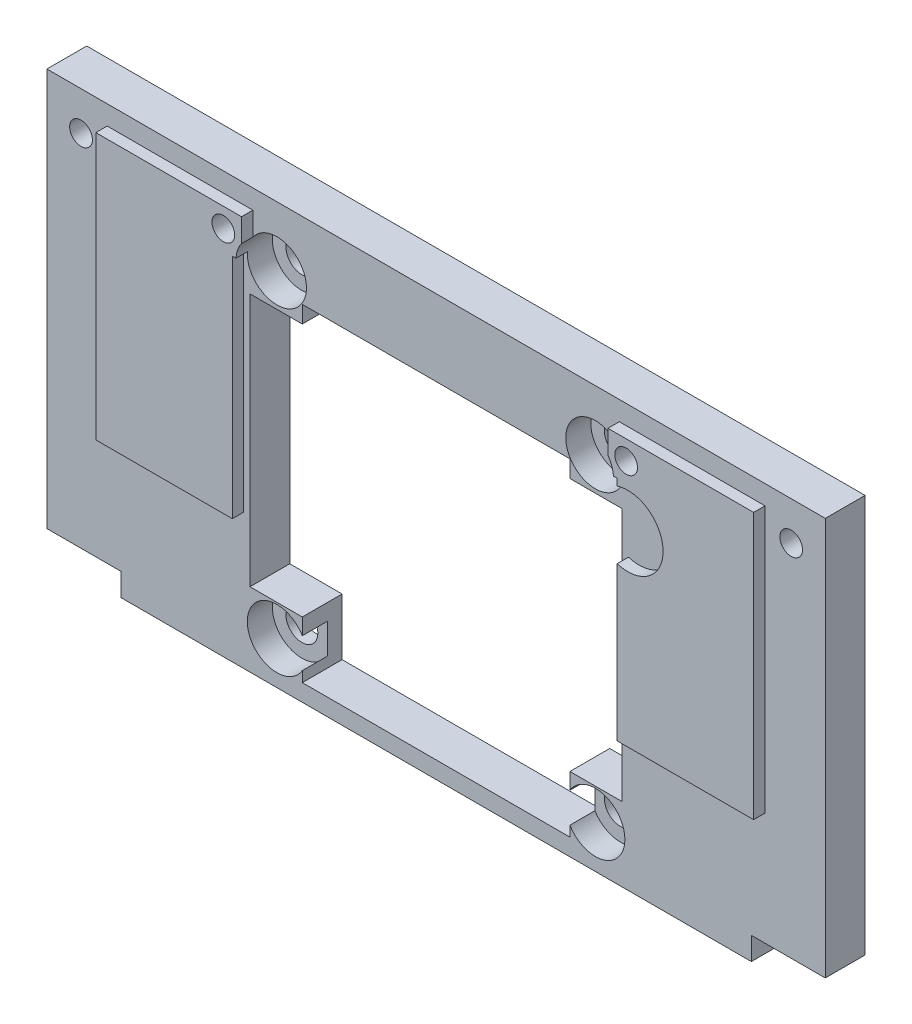
SolidWorks part; units mm, degrees
ref_plane "Front Plane" through (0, 0, 0) normal (0, 0, 1) x (1, 0, 0)
ref_plane "Top Plane" through (0, 0, 0) normal (0, 1, 0) x (1, 0, 0)
ref_plane "Right Plane" through (0, 0, 0) normal (1, 0, 0) x (0, 0, -1)
sketch "Sketch3" plane through (0, 0, 0) normal (0, 0, 1) x (1, 0, 0)
  line L0 (-37.4368, -0.9626) -> (-37.4368, 36.0374)
  line L1 (-3.2168, 30.7779) -> (-3.2168, 32.6429) construction
  line L2 (-34.7809, 21.6224) -> (-21.3928, 21.6224) construction
  line L3 (-30.5893, -0.9626) -> (18.3407, -0.9626) construction
  line L4 (-9.7818, 10.2129) -> (-9.7818, 23.3429) construction
  line L5 (-9.7818, 23.3429) -> (3.3482, 23.3429) construction
  line L6 (3.3482, 23.3429) -> (3.3482, 10.2129) construction
  line L7 (3.3482, 10.2129) -> (-9.7818, 10.2129) construction
  line L9 (-37.4368, -0.9626) -> (-14.8318, -0.9626)
  line L10 (-14.9818, 0.5374) -> (-14.9818, 5.5374)
  line L11 (-14.9818, 29.3429) -> (8.5482, 29.3429)
  line L12 (8.5482, 29.3429) -> (8.5482, 27.8429)
  line L13 (7.2982, -0.9626) -> (31.0032, -0.9626)
  line L14 (31.0032, -0.9626) -> (31.0032, 36.0374)
  line L15 (31.0032, 36.0374) -> (-37.4368, 36.0374)
  line L16 (-34.4368, 32.6429) -> (-20.9268, 32.6429) construction
  line L17 (-20.9268, 32.6429) -> (14.4932, 32.6429) construction
  line L18 (14.4932, 32.6429) -> (28.0032, 32.6429) construction
  line L19 (-17.2168, 30.7779) -> (10.7832, 30.7779) construction
  line L20 (-3.2168, 30.7779) -> (-3.2168, 23.3429) construction
  line L21 (-3.2168, 23.3429) -> (-3.2168, 10.2129) construction
  line L22 (-3.2168, 32.6429) -> (-3.2168, 42.2345) construction
  line L23 (-14.8318, -0.9626) -> (7.2982, -0.9626)
  line L24 (8.5482, 0.5374) -> (-14.9818, 0.5374)
  line L25 (-14.9818, 27.8429) -> (-19.5818, 27.8429)
  line L26 (-19.5818, 27.8429) -> (-19.5818, 5.5374)
  line L27 (-19.5818, 5.5374) -> (-14.9818, 5.5374)
  line L28 (-14.9818, 27.8429) -> (-14.9818, 29.3429)
  line L29 (8.5482, 5.5374) -> (13.1482, 5.5374)
  line L30 (13.1482, 5.5374) -> (13.1482, 27.8429)
  line L31 (13.1482, 27.8429) -> (8.5482, 27.8429)
  line L32 (8.5482, 5.5374) -> (8.5482, 0.5374)
  line L35 (-17.2168, 30.7779) -> (-17.2168, 2.7779) construction
  line L36 (-17.2168, 2.7779) -> (10.7832, 2.7779) construction
  line L37 (10.7832, 2.7779) -> (10.7832, 30.7779) construction
  circle A0 centre (-17.2168, 30.7779) radius 1.4
  circle A1 centre (-34.4368, 32.6429) radius 1
  circle A2 centre (-20.9268, 32.6429) radius 1
  circle A3 centre (14.4932, 32.6429) radius 1
  circle A4 centre (28.0032, 32.6429) radius 1
  circle A5 centre (-34.4368, 32.6429) radius 1
  circle A6 centre (-20.9268, 32.6429) radius 1
  circle A7 centre (-17.2168, 30.7779) radius 1.4
  circle A8 centre (-17.2168, 2.7779) radius 1.4
  circle A9 centre (10.7832, 30.7779) radius 1.4
  circle A10 centre (10.7832, 2.7779) radius 1.4
  point P47 (10.8482, 27.8429)
  dimension "D16" = 2
  dimension "D17" = 2.8
  dimension "D1" = 13.51
  dimension "D2" = 35.42
  dimension "D3" = 13.51
  dimension "D4" = 3.3945
  dimension "D5" = 28
  dimension "D6" = 1.865
  dimension "D7" = 13.13
  dimension "D8" = 13.13
  dimension "D9" = 7.435
  dimension "D10" = 3
  dimension "D11" = 3
  dimension "D12" = 5.2
  dimension "D13" = 5.2
  dimension "D14" = 6
  dimension "D15" = 37
  dimension "D18" = 1.5
  dimension "D19" = 5
  dimension "D20" = 9.8
  dimension "D22" = 1.5
  dimension "D23" = 9.8
  dimension "D24" = 28
extrude "Boss-Extrude1" add sketch "Sketch3" along normal blind 3.5 contours L14 L15 L0 L9 L10 L11 L12 L13 A9 A4 A3 A2 A1 A0
sketch "Sketch13" plane through (0, 0, 0) normal (0, 0, -1) x (-1, 0, 0)
  line L0 (-31.0032, 36.0374) -> (37.4368, 36.0374) construction
  line L1 (-31.0032, 36.0374) -> (-16.1332, 36.0374)
  line L2 (-31.0032, 36.0374) -> (-31.0032, -0.9626)
  line L3 (-31.0032, -0.9626) -> (-16.1332, -0.9626)
  line L4 (-16.1332, 36.0374) -> (-16.1332, -0.9626)
  line L5 (37.4368, -0.9626) -> (-31.0032, -0.9626) construction
  line L7 (22.5668, 36.0374) -> (37.4368, 36.0374)
  line L8 (22.5668, 36.0374) -> (22.5668, -0.9626)
  line L9 (22.5668, -0.9626) -> (37.4368, -0.9626)
  line L10 (37.4368, 36.0374) -> (37.4368, -0.9626)
  line L11 (3.2168, 36.0374) -> (3.2168, 44.4839) construction
  line L12 (3.2168, 36.0374) -> (-16.1332, 36.0374) construction
  line L13 (3.2168, 36.0374) -> (22.5668, 36.0374) construction
  line L14 (-31.0032, -0.9626) -> (-31.0032, 36.0374) construction
  dimension "D1" = 38.7
extrude "Boss-Extrude3" [suppressed] add sketch "Sketch13" along normal blind 1
sketch "Sketch9" plane through (0, 0, 3.5) normal (0, 0, -1) x (-1, 0, 0)
  circle A0 centre (-10.7832, 30.7779) radius 2.6
  circle A1 centre (17.2168, 30.7779) radius 2.6
  circle A2 centre (-10.7832, 2.7779) radius 2.6
  circle A3 centre (17.2168, 2.7779) radius 2.6
  dimension "D1" = 5.2
extrude "Cut-Extrude1" cut sketch "Sketch9" along normal blind 2.2
sketch "Sketch10" plane through (0, 0, 0) normal (0, 0, -1) x (-1, 0, 0)
  line L0 (14.9818, 29.3429) -> (-8.5482, 29.3429) construction
  line L1 (-6.7832, 31.8429) -> (13.2168, 31.8429)
  line L2 (-6.7832, 31.8429) -> (-6.7832, 29.3429)
  line L3 (-6.7832, 29.3429) -> (13.2168, 29.3429)
  line L4 (13.2168, 31.8429) -> (13.2168, 29.3429)
  point P4 (3.2168, 29.3429)
  dimension "D1" = 2.5
  dimension "D2" = 20
extrude "Cut-Extrude2" cut sketch "Sketch10" against normal blind 1.75
sketch "Sketch11" plane through (0, 0, 3.5) normal (0, 0, 1) x (1, 0, 0)
  line L0 (-34.4368, 32.6429) -> (-20.9268, 32.6429) construction
  line L1 (-32.1368, 30.9429) -> (-32.1368, 10.9429)
  line L9 (-19.3268, 34.3429) -> (-32.1368, 34.3429)
  line L14 (-32.1368, 30.9429) -> (-32.1368, 34.3429)
  line L17 (-32.1368, 10.9429) -> (-20.1368, 10.9429)
  line L18 (-20.1368, 30.9429) -> (-20.1368, 10.9429)
  line L19 (-27.6818, 10.9429) -> (-27.6818, 4.0347) construction
  line L20 (-19.3268, 34.3429) -> (-19.3268, 32.2971)
  line L21 (-20.1368, 30.9429) -> (-19.8116, 30.9429)
  circle A1 centre (-34.4368, 32.6429) radius 1 construction
  circle A2 centre (-20.9268, 32.6429) radius 1
  circle A5 centre (-20.9268, 32.6429) radius 1 construction
  arc A6 (-19.3268, 32.2971) -> (-19.8116, 30.9429) centre (-17.2168, 30.7779) ccw
  point P2 (-27.6818, 32.6429)
  point P16 (-32.1368, 32.6429)
  dimension "D1" = 1.6
  dimension "D2" = 12
  dimension "D3" = 2.3
  dimension "D5" = 20
extrude "Boss-Extrude2" add sketch "Sketch11" along normal blind 1
ref_plane "Plane1" through (-3.2168, 0, 0) normal (-1, 0, 0) x (0, 0, 1)
mirror "Mirror1" about plane through (-3.2168, 0, 0) normal (-1, 0, 0) of "Boss-Extrude2"
sketch "Sketch14" plane through (0, 0, 4.5) normal (0, 0, 1) x (1, 0, 0)
  circle A1 centre (14.6422, 27.3923) radius 3.1
  circle A2 centre (14.4932, 32.6429) radius 1 construction
  circle A3 centre (28.0032, 32.6429) radius 1 construction
  dimension "D1" = 6.2
  dimension "D2" = 5.2506
  dimension "D3" = 13.361
extrude "Cut-Extrude3" cut sketch "Sketch14" against normal up to surface (1 mm away) up to face at (16.1681, 26.148, 3.5)
sketch "Sketch15" plane through (0, 0, 3.5) normal (0, 0, 1) x (1, 0, 0)
  line L1 (-37.4368, -0.9626) -> (-30.9368, -0.9626)
  line L2 (-37.4368, -0.9626) -> (-37.4368, 1.0374)
  line L3 (-37.4368, 1.0374) -> (-30.9368, 1.0374)
  line L4 (-30.9368, -0.9626) -> (-30.9368, 1.0374)
  line L5 (31.0032, -0.9626) -> (24.5032, -0.9626)
  line L6 (31.0032, -0.9626) -> (31.0032, 1.0374)
  line L7 (31.0032, 1.0374) -> (24.5032, 1.0374)
  line L8 (24.5032, -0.9626) -> (24.5032, 1.0374)
  dimension "D1" = 6.5
  dimension "D2" = 2
extrude "Cut-Extrude4" cut sketch "Sketch15" against normal through all
